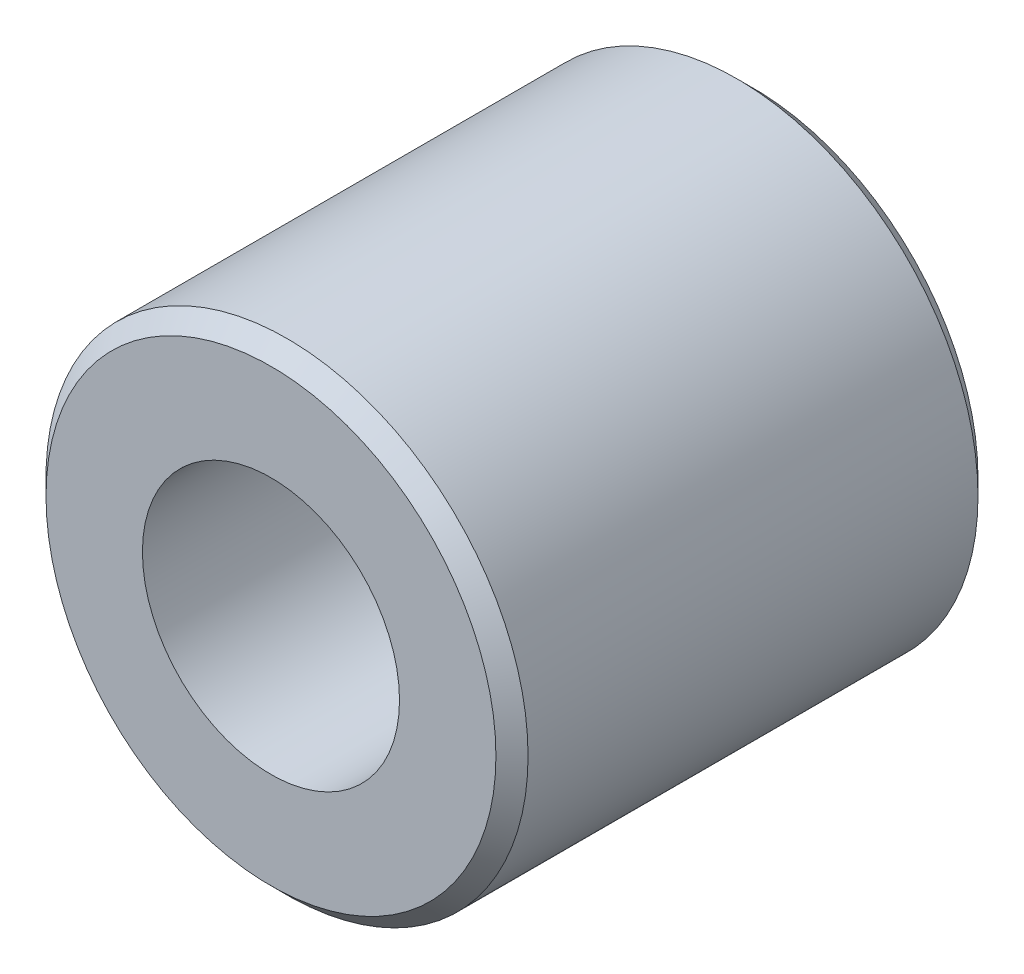
SolidWorks part; units mm, degrees
ref_plane "前视基准面" through (0, 0, 0) normal (0, 0, 1) x (1, 0, 0)
ref_plane "上视基准面" through (0, 0, 0) normal (0, 1, 0) x (1, 0, 0)
ref_plane "右视基准面" through (0, 0, 0) normal (1, 0, 0) x (0, 0, -1)
sketch "草图1" plane through (0, 0, 0) normal (0, 0, 1) x (1, 0, 0)
  circle A0 centre (0, 0) radius 7.5
  circle A1 centre (0, 0) radius 4
  dimension "D1" = 15
  dimension "D2" = 8
extrude "凸台-拉伸1" add sketch "草图1" along normal mid plane 15
chamfer "倒角1" distance 0.5 angle 45 1 edges at (7.5, 0, -7.5)
chamfer "倒角2" distance 0.5 angle 45 1 edges at (7.5, 0, 7.5)
